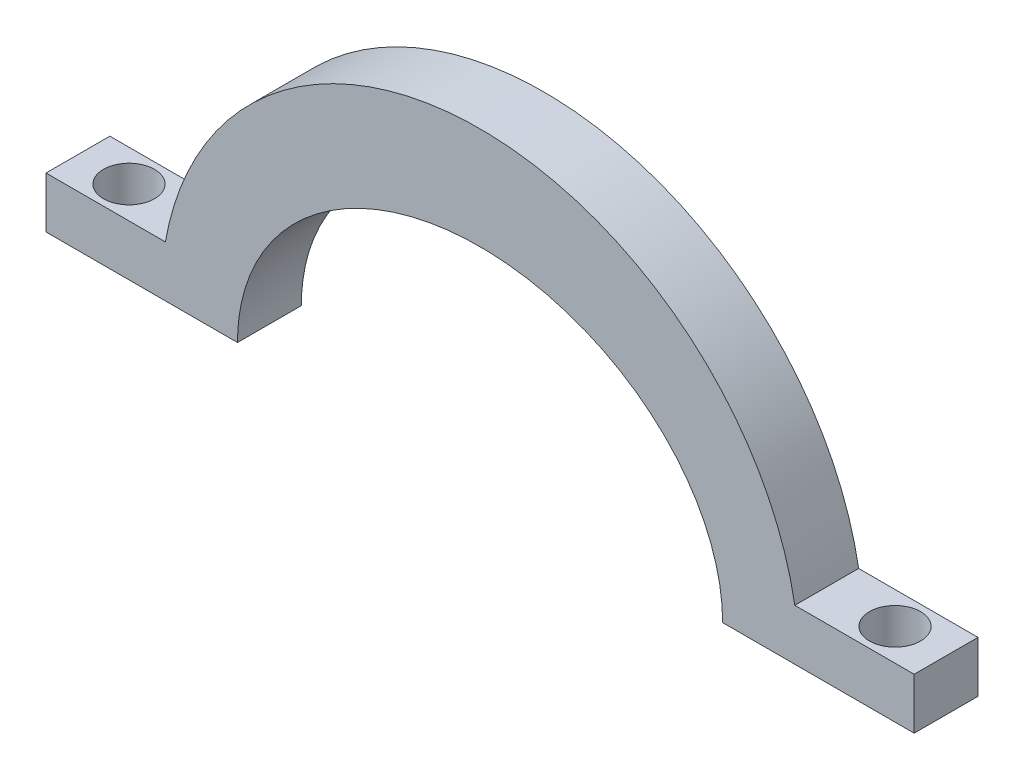
SolidWorks part; units mm, degrees
ref_plane "Front Plane" through (0, 0, 0) normal (0, 0, 1) x (1, 0, 0)
ref_plane "Top Plane" through (0, 0, 0) normal (0, 1, 0) x (1, 0, 0)
ref_plane "Right Plane" through (0, 0, 0) normal (1, 0, 0) x (0, 0, -1)
sketch "Sketch1" plane through (0, 0, 0) normal (0, 0, 1) x (1, 0, 0)
  line L0 (-25, 0) -> (25, 0)
  ellipse E0 centre (0, 0) end of major axis (19, 0) minor radius 16
  ellipse E1 centre (0, 0) end of major axis (25, 0) minor radius 24
  dimension "D1" = 38
  dimension "D2" = 32
  dimension "D3" = 50
  dimension "D4" = 48
extrude "Boss-Extrude1" add sketch "Sketch1" along normal blind 5 contours L0 E1 E0
sketch "Sketch2" plane through (0, 0, 0) normal (0, -1, 0) x (1, 0, 0)
  line L0 (0, 0) -> (0, 5) construction
  line L1 (-19, 5) -> (-34, 5)
  line L2 (-19, 5) -> (-19, 0)
  line L3 (-19, 0) -> (-34, 0)
  line L4 (-34, 5) -> (-34, 0)
  line L5 (19, 5) -> (-19, 5) construction
  line L6 (19, 5) -> (19, 0)
  line L7 (19, 0) -> (34, 0)
  line L8 (34, 5) -> (34, 0)
  line L9 (19, 5) -> (34, 5)
  dimension "D1" = 15
extrude "Boss-Extrude2" add sketch "Sketch2" against normal blind 4
sketch "Sketch3" plane through (0, 0, 0) normal (0, -1, 0) x (1, 0, 0)
  line L0 (-34, 5) -> (-34, 0) construction
  line L1 (-34, 0) -> (-19, 0) construction
  line L2 (0, 0) -> (0, 5) construction
  line L3 (19, 5) -> (-19, 5) construction
  circle A0 centre (-30, 2.5) radius 2
  circle A1 centre (30, 2.5) radius 2
  dimension "D1" = 4
  dimension "D2" = 4
  dimension "D3" = 2.5
extrude "Cut-Extrude1" cut sketch "Sketch3" against normal through all
